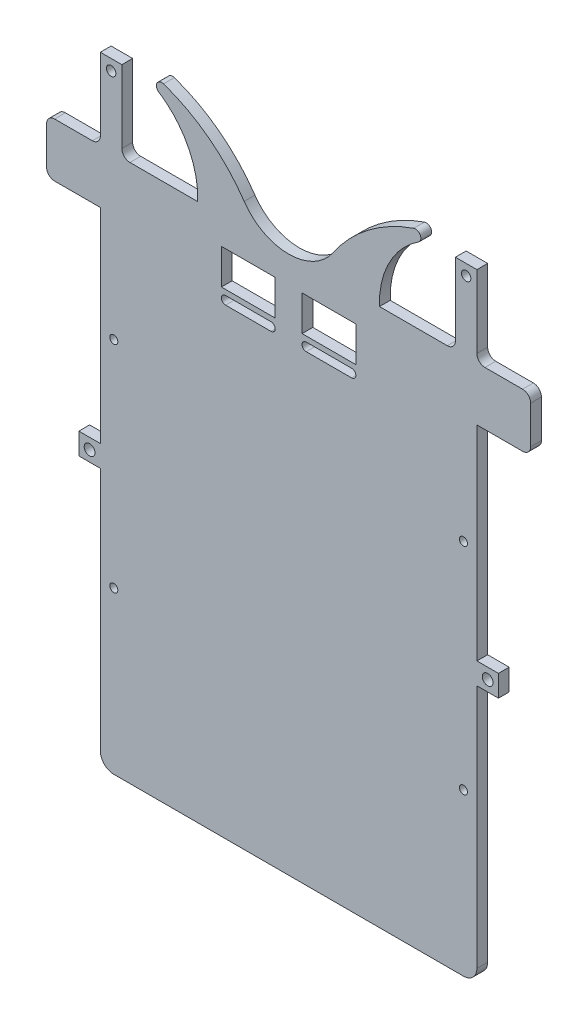
SolidWorks part; units mm, degrees
ref_plane "前视基准面" through (0, 0, 0) normal (0, 0, 1) x (1, 0, 0)
ref_plane "上视基准面" through (0, 0, 0) normal (0, 1, 0) x (1, 0, 0)
ref_plane "右视基准面" through (0, 0, 0) normal (1, 0, 0) x (0, 0, -1)
sketch "草图1" plane through (0, 0, 0) normal (0, 0, 1) x (1, 0, 0)
  line L0 (-38.6497, 0) -> (37.2518, 0) construction
  line L1 (-70, 100) -> (70, 100)
  line L2 (-70, 100) -> (-70, -100)
  line L3 (-70, -100) -> (70, -100)
  line L4 (70, 100) -> (70, -100)
  line L5 (-70, 100) -> (70, -100) construction
  line L6 (-70, -100) -> (70, 100) construction
  line L7 (0, 33.0222) -> (0, -43.9262) construction
  circle A0 centre (-65, 40) radius 1.5
  circle A1 centre (-65, -40) radius 1.5
  circle A2 centre (65, -40) radius 1.5
  circle A3 centre (65, 40) radius 1.5
  point P0 (0, 0)
  dimension "D3" = 5
  dimension "D4" = 3
  dimension "D1" = 140
  dimension "D2" = 200
  dimension "D5" = 40
extrude "凸台-拉伸1" add sketch "草图1" along normal blind 4
sketch "草图2" plane through (0, 0, 4) normal (0, 0, 1) x (1, 0, 0)
  line L0 (70, -100) -> (70, 100) construction
  line L1 (70, 100) -> (90, 100)
  line L2 (70, 100) -> (70, 80)
  line L3 (70, 80) -> (90, 80)
  line L4 (90, 100) -> (90, 80)
  dimension "D1" = 20
  dimension "D2" = 20
extrude "凸台-拉伸2" add sketch "草图2" against normal blind 4
fillet "圆角1" radius 3 2 edges at (90, 100, 2) (90, 80, 2)
mirror "镜向1" about plane through (0, 0, 0) normal (1, 0, 0) of "凸台-拉伸2", "圆角1"
sketch "草图3" plane through (0, 0, 4) normal (0, 0, 1) x (1, 0, 0)
  line L0 (87, 100) -> (-87, 100) construction
  line L1 (-70, 100) -> (-62, 100)
  line L2 (-70, 100) -> (-70, 130)
  line L3 (-70, 130) -> (-62, 130)
  line L4 (-62, 100) -> (-62, 130)
  circle A0 centre (-66, 126) radius 1.75
  dimension "D3" = 3.5
  dimension "D1" = 8
  dimension "D2" = 30
  dimension "D4" = 4
extrude "凸台-拉伸3" add sketch "草图3" against normal blind 4
fillet "圆角2" radius 3 2 edges at (-62, 100, 2) (-70, 100, 2)
mirror "镜向2" about plane through (0, 0, 0) normal (1, 0, 0) of "凸台-拉伸3", "圆角2"
fillet "圆角3" radius 5 2 edges at (-70, -100, 2) (70, -100, 2)
sketch "草图4" plane through (0, 0, 0) normal (0, 0, -1) x (-1, 0, 0)
  line L1 (-59, 100) -> (59, 100) construction
  line L2 (0, 120) -> (0, 43.57) construction
  line L3 (-33.7864, 100) -> (33.7864, 100)
  arc A0 (-16.5072, 108.7078) -> (16.5072, 108.7078) centre (0, 120) ccw
  arc A1 (46.5063, 131.5664) -> (16.5072, 108.7078) centre (66.0287, 74.8313) ccw
  arc A2 (48.2539, 128.0028) -> (46.5063, 131.5664) centre (47.157, 129.6752) ccw
  arc A3 (-48.2539, 128.0028) -> (-46.5063, 131.5664) centre (-47.157, 129.6752) cw
  arc A4 (-46.5063, 131.5664) -> (-16.5072, 108.7078) centre (-66.0287, 74.8313) cw
  spline S0 degree 3 poles (33.7864, 100) (33.3848, 111.2431) (38.9442, 121.8971) (48.2539, 128.0028) knots 0 0 0 0 0.661941 0.661941 0.661941 0.661941
  spline S1 degree 3 poles (-33.7864, 100) (-33.3848, 111.2431) (-38.9442, 121.8971) (-48.2539, 128.0028) knots 0 0 0 0 0.661941 0.661941 0.661941 0.661941
  line M16 (59, 100) -> (-59, 100)
  dimension "D1" = 40
  dimension "D2" = 120
  dimension "D3" = 2
extrude "凸台-拉伸4" add sketch "草图4" against normal blind 4 contours S1 L3 A0 A4 A3 | S0 A2 A1 A0 M16
sketch "草图5" plane through (0, 0, 4) normal (0, 0, 1) x (1, 0, 0)
  line L0 (0, 0) -> (-80.4049, 0) construction
  line L1 (0, 19.3393) -> (0, 0) construction
  line L2 (-70, 80) -> (-70, -95) construction
  line L3 (-78, 4) -> (-70, 4)
  line L4 (-78, 4) -> (-78, -4)
  line L5 (-78, -4) -> (-70, -4)
  line L6 (-70, 4) -> (-70, -4)
  line L7 (70, 4) -> (70, -4)
  line L8 (78, -4) -> (70, -4)
  line L9 (78, 4) -> (78, -4)
  line L10 (78, 4) -> (70, 4)
  circle A0 centre (-74, 0) radius 2
  circle A1 centre (74, 0) radius 2
  dimension "D4" = 4
  dimension "D1" = 8
  dimension "D2" = 4
  dimension "D3" = 8
extrude "凸台-拉伸5" add sketch "草图5" against normal blind 4
sketch "草图6" plane through (0, 0, 4) normal (0, 0, 1) x (1, 0, 0)
  line L0 (0, 100) -> (0, 0) construction
  line L1 (-25, 90) -> (-5, 90)
  line L2 (-25, 90) -> (-25, 76.9)
  line L3 (-25, 76.9) -> (-5, 76.9)
  line L4 (25, 90) -> (25, 76.9)
  line L5 (-33.7864, 100) -> (-59, 100) construction
  line L6 (-5, 90) -> (-5, 76.9)
  line L7 (5, 90) -> (5, 76.9)
  line L8 (5, 90) -> (25, 90)
  line L9 (5, 76.9) -> (25, 76.9)
  line L10 (-23.45, 74.95) -> (-6.55, 74.95)
  line L11 (-23.45, 71.85) -> (-6.55, 71.85)
  line L12 (23.45, 71.85) -> (6.55, 71.85)
  line L13 (23.45, 74.95) -> (6.55, 74.95)
  arc A0 (-16.5072, 108.7078) -> (16.5072, 108.7078) centre (0, 120) ccw construction
  arc A1 (-23.45, 74.95) -> (-23.45, 71.85) centre (-23.45, 73.4) ccw
  arc A2 (-6.55, 71.85) -> (-6.55, 74.95) centre (-6.55, 73.4) ccw
  arc A3 (23.45, 74.95) -> (23.45, 71.85) centre (23.45, 73.4) cw
  arc A4 (6.55, 71.85) -> (6.55, 74.95) centre (6.55, 73.4) cw
  dimension "D7" = 3.1
  dimension "D8" = 3.1
  dimension "D1" = 10
  dimension "D2" = 13.1
  dimension "D3" = 50
  dimension "D4" = 25
  dimension "D5" = 5
  dimension "D6" = 5
  dimension "D9" = 1.55
  dimension "D10" = 1.55
  dimension "D11" = 3.5
extrude "切除-拉伸1" cut sketch "草图6" against normal blind 10
